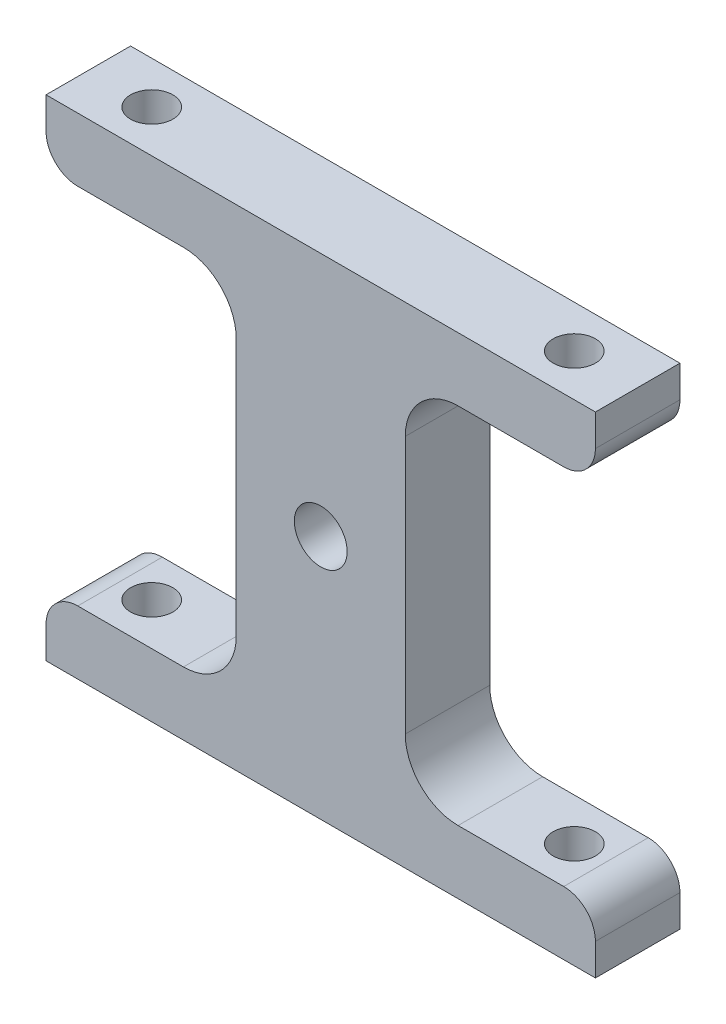
SolidWorks part; units mm, degrees
material "6061 合金"
ref_plane "前视基准面" through (0, 0, 0) normal (0, 0, 1) x (1, 0, 0)
ref_plane "上视基准面" through (0, 0, 0) normal (0, 1, 0) x (1, 0, 0)
ref_plane "右视基准面" through (0, 0, 0) normal (1, 0, 0) x (0, 0, -1)
sketch "草图1" plane through (0, 0, 0) normal (0, 0, 1) x (1, 0, 0)
  line L0 (0, 0) -> (0, 69.0225) construction
  line L1 (-8, -17.2) -> (-8, 17.2)
  line L2 (-8, 17.2) -> (-26, 17.2)
  line L3 (-26, 17.2) -> (-26, 23.2)
  line L4 (-26, 23.2) -> (26, 23.2)
  line L5 (26, 23.2) -> (26, 17.2)
  line L6 (26, 17.2) -> (8, 17.2)
  line L7 (8, 17.2) -> (8, -17.2)
  line L13 (0, 0) -> (-19.0914, 0) construction
  line L14 (-8, -17.2) -> (-26, -17.2)
  line L15 (26, -17.2) -> (8, -17.2)
  line L16 (26, -23.2) -> (26, -17.2)
  line L17 (-26, -17.2) -> (-26, -23.2)
  line L18 (-26, -23.2) -> (26, -23.2)
  circle A0 centre (0, 0) radius 2.5
  dimension "D1" = 5
  dimension "D2" = 8
  dimension "D3" = 8
  dimension "D4" = 23.2
  dimension "D6" = 6
  dimension "D7" = 6
  dimension "D8" = 52
extrude "凸台-拉伸1" add sketch "草图1" along normal blind 8
sketch "草图2" plane through (0, 23.2, 0) normal (0, 1, 0) x (1, 0, 0)
  line L0 (-26, -4) -> (26, -4) construction
  line L1 (-26, -8) -> (-26, 0) construction
  line L2 (26, -8) -> (26, 0) construction
  line L3 (0, 0) -> (0, -8) construction
  line L4 (26, -8) -> (-26, -8) construction
  circle A0 centre (-20, -4) radius 2
  circle A1 centre (20, -4) radius 2
  dimension "D1" = 4
  dimension "D3" = 4
  dimension "D2" = 20
  dimension "D4" = 20
extrude "切除-拉伸1" cut sketch "草图2" against normal through all
fillet "圆角1" radius 3 4 edges at (26, -17.2, 4) (-26, -17.2, 4) (26, 17.2, 4) (-26, 17.2, 4)
fillet "圆角2" radius 5 4 edges at (-8, -17.2, 4) (8, -17.2, 4) (8, 17.2, 4) (-8, 17.2, 4)
